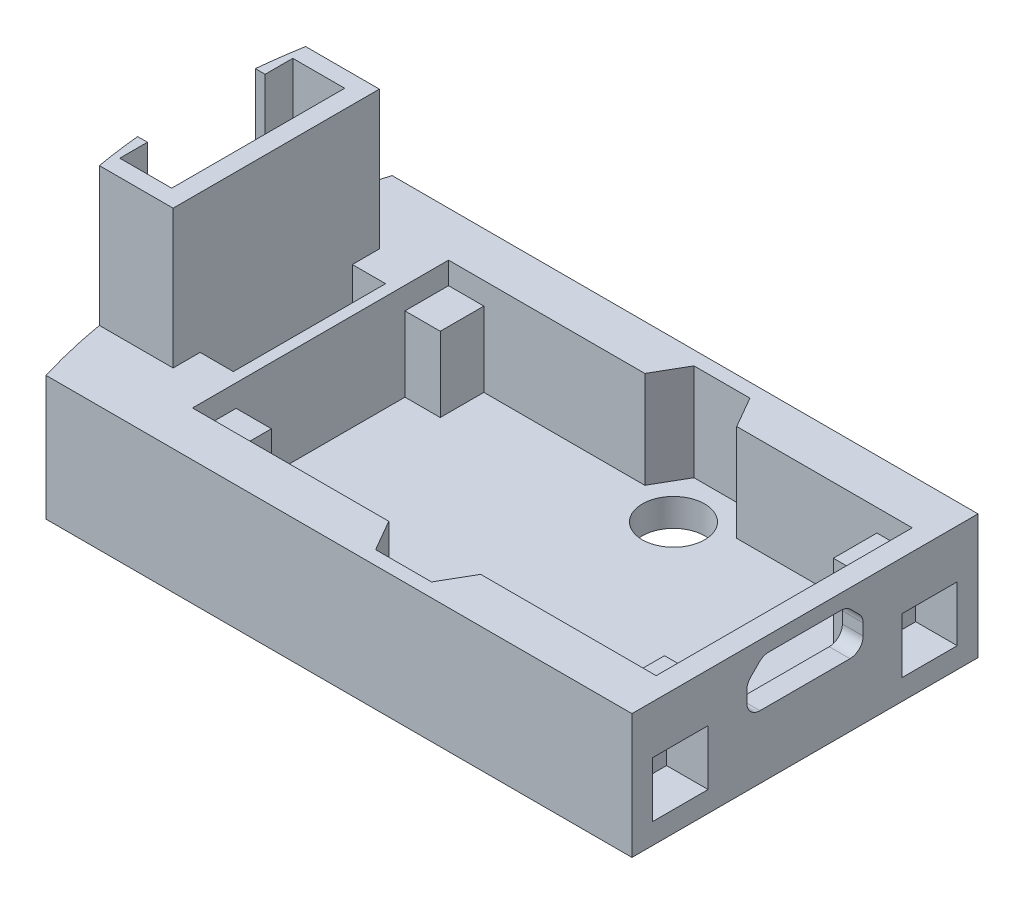
SolidWorks part; units mm, degrees
ref_plane "Front Plane" through (0, 0, 0) normal (0, 0, 1) x (1, 0, 0)
ref_plane "Top Plane" through (0, 0, 0) normal (0, 1, 0) x (1, 0, 0)
ref_plane "Right Plane" through (0, 0, 0) normal (1, 0, 0) x (0, 0, -1)
sketch "Sketch1" plane through (0, 0, 0) normal (0, 1, 0) x (1, 0, 0)
  line L0 (-129.5212, 0) -> (129.5212, 0) construction
  line L5 (-20.75, 15) -> (20.75, 15)
  line L6 (-20.75, 15) -> (-20.75, -15) construction
  line L7 (-20.75, -15) -> (20.75, -15)
  line L8 (20.75, 15) -> (20.75, -15)
  line L9 (-20.75, 15) -> (20.75, -15) construction
  line L10 (-20.75, -15) -> (20.75, 15) construction
  line L11 (0, 15) -> (0, -15) construction
  line L12 (-23.4213, 18.3369) -> (-23.4213, -18.3369) construction
  arc A0 (-20.75, -15) -> (-20.75, 15) centre (20.0287, 0) cw
  point P5 (0, 0)
  point P13 (0, 0)
  point P17 (0, 0)
  point P20 (-23.4213, 0)
  point P23 (41.95, 0)
  dimension "D3" = 43.45
  dimension "D1" = 41.5
  dimension "D2" = 30
extrude "Boss-Extrude1" add sketch "Sketch1" along normal blind 9
sketch "Sketch17" plane through (0, 9, 0) normal (0, 1, 0) x (1, 0, 0)
  line L0 (20.75, -15) -> (20.75, 15) construction
  line L1 (-14.25, -9.25) -> (19.25, -9.25)
  line L2 (-14.25, -9.25) -> (-14.25, 9.25)
  line L3 (-14.25, 9.25) -> (19.25, 9.25)
  line L4 (19.25, -9.25) -> (19.25, 9.25)
  line L8 (-14.25, 0) -> (19.25, 0) construction
  line L9 (-10.45, 0) -> (10.45, 0) construction
  dimension "D1" = 18.5
  dimension "D2" = 33.5
  dimension "D3" = 1.5
extrude "Cut-Extrude8" cut sketch "Sketch17" against normal offset from surface (7 mm away) 2 up to face at (-0.6678, 0, 0)
sketch "Sketch18" plane through (0, 2, 0) normal (0, 1, 0) x (1, 0, 0)
  line L1 (-14.25, 9.25) -> (-11.7, 9.25)
  line L2 (-14.25, 9.25) -> (-14.25, 6.1)
  line L3 (-14.25, 6.1) -> (-11.7, 6.1)
  line L4 (-11.7, 9.25) -> (-11.7, 6.1)
  line L5 (-14.25, -9.25) -> (-11.7, -9.25)
  line L6 (-14.25, -9.25) -> (-14.25, -6.1)
  line L7 (-14.25, -6.1) -> (-11.7, -6.1)
  line L8 (-11.7, -9.25) -> (-11.7, -6.1)
  line L9 (19.25, 9.25) -> (16.7, 9.25)
  line L10 (19.25, 9.25) -> (19.25, 6.1)
  line L11 (19.25, 6.1) -> (16.7, 6.1)
  line L12 (16.7, 9.25) -> (16.7, 6.1)
  line L13 (19.25, -9.25) -> (16.7, -9.25)
  line L14 (19.25, -9.25) -> (19.25, -6.1)
  line L15 (19.25, -6.1) -> (16.7, -6.1)
  line L16 (16.7, -9.25) -> (16.7, -6.1)
  dimension "D1" = 3.15
  dimension "D2" = 2.55
  dimension "D3" = 2.55
  dimension "D4" = 3.15
  dimension "D5" = 3.15
  dimension "D6" = 2.55
  dimension "D7" = 2.55
  dimension "D8" = 3.15
extrude "Boss-Extrude2" add sketch "Sketch18" along normal offset from surface (5.4 mm away) 1.6 up to face at (2.5, 9, 0)
sketch "Sketch25" plane through (20.75, 0, 0) normal (1, 0, 0) x (0, 0, -1)
  line L6 (0, 4.95) -> (0, -4.95) construction
  line B0 (3.5682, 6.6462) -> (2.9354, 7.2791) construction
  line B1 (3.7, 5.5109) -> (3.7, 6.328) construction
  line B2 (-3.25, 5.0609) -> (3.25, 5.0609) construction
  line B3 (-3.7, 6.328) -> (-3.7, 5.5109) construction
  line B4 (-2.9354, 7.2791) -> (-3.5682, 6.6462) construction
  line B5 (-2.6, 7.4109) -> (2.6, 7.4109) construction
  line B6 (3.745, 6.823) -> (3.1121, 7.4559) construction
  line B7 (-3.95, 6.3283) -> (-3.95, 5.5109) construction
  line B8 (-3.25, 4.8109) -> (3.25, 4.8109) construction
  line B9 (3.95, 5.5109) -> (3.95, 6.3292) construction
  line B10 (-3.1121, 7.4559) -> (-3.745, 6.823) construction
  line B11 (-2.6172, 7.6609) -> (2.6172, 7.6609) construction
  line B12 (-3.95, 6.3286) -> (-3.95, 6.3283) construction
  line B13 (3.95, 6.3303) -> (3.95, 6.3292) construction
  line B14 (0, 7.6609) -> (0, 4.8109) construction
  arc B15 (2.9354, 7.2791) -> (2.6172, 7.4109) centre (2.6172, 6.9609) ccw construction
  arc B16 (3.7, 6.3309) -> (3.5682, 6.6462) centre (3.25, 6.328) ccw construction
  arc B17 (3.25, 5.0609) -> (3.7, 5.5109) centre (3.25, 5.5109) ccw construction
  arc B18 (-3.7, 5.5109) -> (-3.25, 5.0609) centre (-3.25, 5.5109) ccw construction
  arc B19 (-3.5682, 6.6462) -> (-3.7, 6.3309) centre (-3.25, 6.328) ccw construction
  arc B20 (-2.6172, 7.4109) -> (-2.9354, 7.2791) centre (-2.6172, 6.9609) ccw construction
  arc B21 (3.95, 6.3303) -> (3.745, 6.823) centre (3.25, 6.328) ccw construction
  arc B22 (3.1121, 7.4559) -> (2.6172, 7.6609) centre (2.6172, 6.9609) ccw construction
  arc B23 (-3.95, 5.5109) -> (-3.25, 4.8109) centre (-3.25, 5.5109) ccw construction
  arc B24 (3.25, 4.8109) -> (3.95, 5.5109) centre (3.25, 5.5109) ccw construction
  arc B25 (-2.6172, 7.6609) -> (-3.1121, 7.4559) centre (-2.6172, 6.9609) ccw construction
  arc B26 (-3.745, 6.823) -> (-3.95, 6.3286) centre (-3.25, 6.328) ccw construction
  line B27 (-3.1121, 7.4559) -> (-3.745, 6.823) construction
  line B28 (-3.95, 6.328) -> (-3.95, 5.5109) construction
  line B29 (-3.25, 4.8109) -> (3.25, 4.8109) construction
  line B30 (-2.6, 7.1609) -> (2.6, 7.1609) construction
  line B31 (3.745, 6.823) -> (3.1121, 7.4559) construction
  line B32 (3.95, 5.5109) -> (3.95, 6.328) construction
  line B33 (-0.25, 7.6609) -> (-0.25, 4.8109) construction
  line B34 (3.9218, 6.9998) -> (3.2889, 7.6326)
  line B35 (-2.6172, 7.9109) -> (2.6172, 7.9109)
  line B36 (-3.2889, 7.6326) -> (-3.9218, 6.9998)
  line B37 (-4.2, 6.3288) -> (-4.2, 6.3284)
  line B38 (-4.2, 6.3284) -> (-4.2, 5.5109)
  line B39 (-3.25, 4.5609) -> (3.25, 4.5609)
  line B40 (4.2, 5.5109) -> (4.2, 6.3295)
  line B41 (4.2, 6.331) -> (4.2, 6.3295)
  arc B42 (3.2889, 7.6326) -> (2.6172, 7.9109) centre (2.6172, 6.9609) ccw
  arc B43 (-2.6172, 7.9109) -> (-3.2889, 7.6326) centre (-2.6172, 6.9609) ccw
  arc B44 (-3.9218, 6.9998) -> (-4.2, 6.3288) centre (-3.25, 6.328) ccw
  arc B45 (-4.2, 5.5109) -> (-3.25, 4.5609) centre (-3.25, 5.5109) ccw
  arc B46 (3.25, 4.5609) -> (4.2, 5.5109) centre (3.25, 5.5109) ccw
  arc B47 (4.2, 6.331) -> (3.9218, 6.9998) centre (3.25, 6.328) ccw
sketch_block_instance "Block1-1"
sketch_block "Block1" parameters "D1"=0.25
extrude "Cut-Extrude13" cut sketch "Sketch25" against normal up to next
sketch "Sketch27" plane through (0, 2, 0) normal (0, 1, 0) x (1, 0, 0)
  line L0 (3.25, -12) -> (3.25, 12) construction
  line L1 (-20.75, -15) -> (20.75, -15) construction
  line L3 (-14.25, 9.25) -> (-14.25, -9.25) construction
  line L5 (-3.25, 0) -> (3.25, 0) construction
  circle A0 centre (3.25, -8) radius 2.25
  circle A1 centre (3.25, 8) radius 2.25
  point P14 (0, 0)
  dimension "D1" = 4.5
  dimension "D2" = 7
  dimension "D3" = 17.5
extrude "Cut-Extrude15" cut sketch "Sketch27" against normal up to next
sketch "Sketch26" plane through (0, 9, 0) normal (0, 1, 0) x (1, 0, 0)
  line L3 (-5.75, 0) -> (5.75, 0) construction
  line L4 (5.2707, -4.5) -> (1.2293, -4.5)
  line L5 (1.2293, -4.5) -> (-0.7915, -8)
  line L6 (-0.7915, -8) -> (1.2293, -11.5)
  line L7 (1.2293, -11.5) -> (5.2707, -11.5)
  line L8 (5.2707, -11.5) -> (7.2915, -8)
  line L9 (7.2915, -8) -> (5.2707, -4.5)
  line L12 (7.2915, 8) -> (5.2707, 4.5)
  line L13 (5.2707, 11.5) -> (7.2915, 8)
  line L14 (1.2293, 11.5) -> (5.2707, 11.5)
  line L15 (-0.7915, 8) -> (1.2293, 11.5)
  line L16 (1.2293, 4.5) -> (-0.7915, 8)
  line L17 (5.2707, 4.5) -> (1.2293, 4.5)
  circle A0 centre (3.25, -8) radius 3.5 construction
  circle A1 centre (3.25, 8) radius 3.5 construction
  point P18 (0, 0)
  dimension "D1" = 7
extrude "Cut-Extrude14" cut sketch "Sketch26" against normal up to surface (7 mm away) up to face at (2.6875, 2, 0)
sketch "Sketch28" plane through (0, 9, 0) normal (0, 1, 0) x (1, 0, 0)
  line L1 (-14.25, 6.1) -> (-14.25, -6.1) construction
  line L2 (-17.45, -5.5) -> (-15.05, -5.5)
  line L3 (-17.45, -5.5) -> (-17.45, 5.5)
  line L4 (-17.45, 5.5) -> (-15.05, 5.5)
  line L5 (-15.05, -5.5) -> (-15.05, 5.5)
  line L6 (-17.45, -5.5) -> (-15.05, 5.5) construction
  line L7 (-17.45, 5.5) -> (-15.05, -5.5) construction
  line L8 (-23.4213, 0) -> (-14.25, 0) construction
  line L9 (-14.25, 9.25) -> (-14.25, -9.25) construction
  arc A0 (-20.75, 15) -> (-20.75, -15) centre (20.0287, 0) ccw construction
  point P6 (-16.25, 0)
  dimension "D1" = 2.4
  dimension "D2" = 11
  dimension "D3" = 0.8
extrude "Cut-Extrude16" cut sketch "Sketch28" against normal blind 5
ref_plane "Kolo keski" through (-16.25, 0, 0) normal (1, 0, 0) x (0, 0, -1)
sketch "Sketch29" plane through (20.75, 0, 0) normal (1, 0, 0) x (0, 0, -1)
  line L0 (0, 0) -> (0, 9) construction
  line L1 (-11, 1.5) -> (-7, 1.5)
  line L2 (-11, 1.5) -> (-11, 5.5)
  line L3 (-11, 5.5) -> (-7, 5.5)
  line L4 (-7, 1.5) -> (-7, 5.5)
  line L5 (-11, 1.5) -> (-7, 5.5) construction
  line L6 (-11, 5.5) -> (-7, 1.5) construction
  line L7 (-15, 9) -> (15, 9) construction
  line L8 (-9, 9) -> (-9, 0) construction
  line L9 (-15, 0) -> (15, 0) construction
  line L11 (-7.5, 5) -> (-10.5, 5) construction
  line L12 (9, 9) -> (9, 0) construction
  line L13 (11, 5.5) -> (7, 1.5) construction
  line L14 (11, 1.5) -> (7, 5.5) construction
  line L15 (7, 1.5) -> (7, 5.5)
  line L16 (11, 5.5) -> (7, 5.5)
  line L17 (11, 1.5) -> (11, 5.5)
  line L18 (11, 1.5) -> (7, 1.5)
  point P0 (-9, 3.5)
  point P28 (9, 3.5)
  dimension "D1" = 4
  dimension "D2" = 9
  dimension "D3" = 0.5
  dimension "D4" = 4
extrude "Cut-Extrude17" cut sketch "Sketch29" against normal blind 3
sketch "Sketch30" plane through (0, 9, 0) normal (0, 1, 0) x (1, 0, 0)
  line L0 (-22.9694, 6.25) -> (-22.9694, -6.25) construction
  line L1 (-19.4694, -5.5) -> (-19.4694, -6.25)
  line L2 (-22.9694, 6.25) -> (-19.4694, 6.25) construction
  line L3 (-22.9694, 6.25) -> (-22.9694, -6.25) construction
  line L4 (-22.9694, -6.25) -> (-19.4694, -6.25) construction
  line L5 (-19.4694, 6.25) -> (-19.4694, -6.25) construction
  line L6 (-19.4694, -6.25) -> (-22.9694, -6.25)
  line L7 (-19.4694, -5.5) -> (-17.8694, -5.5)
  line L8 (-17.8694, -5.5) -> (-17.8694, -7.85)
  line L9 (-17.8694, -7.85) -> (-22.7063, -7.85)
  line L10 (-17.45, -5.5) -> (-15.05, -5.5) construction
  line L11 (-19.4694, 6.25) -> (-19.4694, 5.45)
  line L13 (-17.8694, 6.65) -> (-17.8694, 7.85)
  line L14 (-17.8694, 7.85) -> (-22.7063, 7.85)
  line L15 (-19.4694, 6.25) -> (-22.9694, 6.25)
  line L16 (-19.4694, 5.45) -> (-19.0694, 5.45)
  line L17 (-19.0694, 5.45) -> (-17.8694, 6.65)
  arc A0 (-20.75, 15) -> (-20.75, -15) centre (20.0287, 0) ccw construction
  arc A1 (-22.9694, -6.25) -> (-22.7063, -7.85) centre (20.0287, 0) ccw
  arc A4 (-22.9694, 6.25) -> (-22.7063, 7.85) centre (20.0287, 0) cw
  dimension "D1" = 12.5
  dimension "D2" = 3.5
  dimension "D3" = 1.6
  dimension "D4" = 1.6
  dimension "D5" = 1.6
  dimension "D6" = 0.8
  dimension "D7" = 0.4
  dimension "D8" = 135
  dimension "D9" = 1.6
extrude "Boss-Extrude3" [suppressed] add sketch "Sketch30" along normal blind 12
sketch "Sketch31" [suppressed] plane through (0, 0, -7.85) normal (0, 0, -1) x (-1, 0, 0)
  line L0 (21.7063, 21) -> (21.7063, 9) construction
  line L1 (16.8694, 9) -> (19.7063, 9)
  line L2 (16.8694, 9) -> (16.8694, 10)
  line L3 (16.8694, 10) -> (19.7063, 10)
  line L4 (19.7063, 9) -> (19.7063, 10)
  line L5 (16.8694, 21) -> (16.8694, 9) construction
  line L6 (16.8694, 15) -> (21.9694, 15)
  line L7 (16.8694, 15) -> (16.8694, 21)
  line L8 (16.8694, 21) -> (21.9694, 21)
  line L9 (21.9694, 15) -> (21.9694, 21)
  dimension "D1" = 1
  dimension "D2" = 2
  dimension "D3" = 5
extrude "Cut-Extrude18" [suppressed] cut sketch "Sketch31" against normal up to next
chamfer "Chamfer1" [suppressed] distance 0.5 angle 45
sketch "Sketch32" plane through (0, 9, 0) normal (0, 1, 0) x (1, 0, 0)
  line L0 (23.4213, 0) -> (-23.4213, 0) construction
  line L1 (-22.005, 6) -> (-23.005, 6) construction
  line L2 (-19.005, 6) -> (-22.005, 6) construction
  line L3 (-19.005, 6) -> (-19.005, -6) construction
  line L4 (-19.005, -6) -> (-22.005, -6) construction
  line L5 (-22.005, 6) -> (-22.005, -6) construction
  line L6 (-19.005, 6) -> (-22.005, -6) construction
  line L7 (-19.005, -6) -> (-22.005, 6) construction
  line L8 (-18.755, 6.25) -> (-22.005, 6.25)
  line L9 (-18.755, 6.25) -> (-18.755, -6.25)
  line L10 (-18.755, -6.25) -> (-22.505, -6.25)
  line L11 (-18.755, -6.25) -> (-22.005, -6.25) construction
  line L12 (-22.505, -6.25) -> (-22.505, -4.25)
  line L13 (-22.505, -4.25) -> (-23.2129, -4.25)
  line L14 (-17.45, -7.45) -> (-22.7778, -7.45)
  line L15 (-17.45, 7.45) -> (-22.7778, 7.45)
  line L16 (-18.755, 6.25) -> (-22.505, 6.25)
  line L17 (-22.505, 6.25) -> (-22.505, 4.25)
  line L18 (-22.505, 4.25) -> (-23.2129, 4.25)
  line L19 (-17.45, 7.45) -> (-17.45, -7.45)
  line L20 (-17.45, 5.5) -> (-17.45, -5.5) construction
  arc A0 (-20.75, 15) -> (-20.75, -15) centre (20.0287, 0) ccw construction
  arc A1 (-23.2129, -4.25) -> (-22.7778, -7.45) centre (20.0287, 0) ccw
  arc A2 (-23.2129, 4.25) -> (-22.7778, 7.45) centre (20.0287, 0) cw
  point P0 (-20.505, 0)
  point P7 (0, 0)
  line M9 (-17.45, -5.5) -> (-17.45, 5.5)
  arc M24 (-20.75, 15) -> (-20.75, -15) centre (20.0287, 0) ccw
  dimension "D1" = 3
  dimension "D2" = 12
  dimension "D3" = 1
  dimension "D5" = 0.5
  dimension "D6" = 2
  dimension "D7" = 1.2
  dimension "D4" = 0.25
extrude "Boss-Extrude4" add sketch "Sketch32" along normal blind 10 contours L19 L15 L18 L17 L16 L8 L9 L10 L12 L13 L14 M24 M9
sketch "Sketch33" plane through (0, 0, 0) normal (0, 1, 0) x (1, 0, 0)
  line L0 (5.2707, 11.5) -> (1.2293, 11.5) construction
  line L1 (-30.5373, 12.5) -> (30.5373, 12.5)
  line L2 (-30.5373, 12.5) -> (-30.5373, -12.5)
  line L3 (-30.5373, -12.5) -> (30.5373, -12.5)
  line L4 (30.5373, 12.5) -> (30.5373, -12.5)
  line L5 (-30.5373, 12.5) -> (30.5373, -12.5) construction
  line L6 (-30.5373, -12.5) -> (30.5373, 12.5) construction
  point P0 (0, 0)
  point P8 (0, 0)
  dimension "D1" = 1
extrude "Cut-Extrude24" cut sketch "Sketch33" along normal through all flip side to cut
